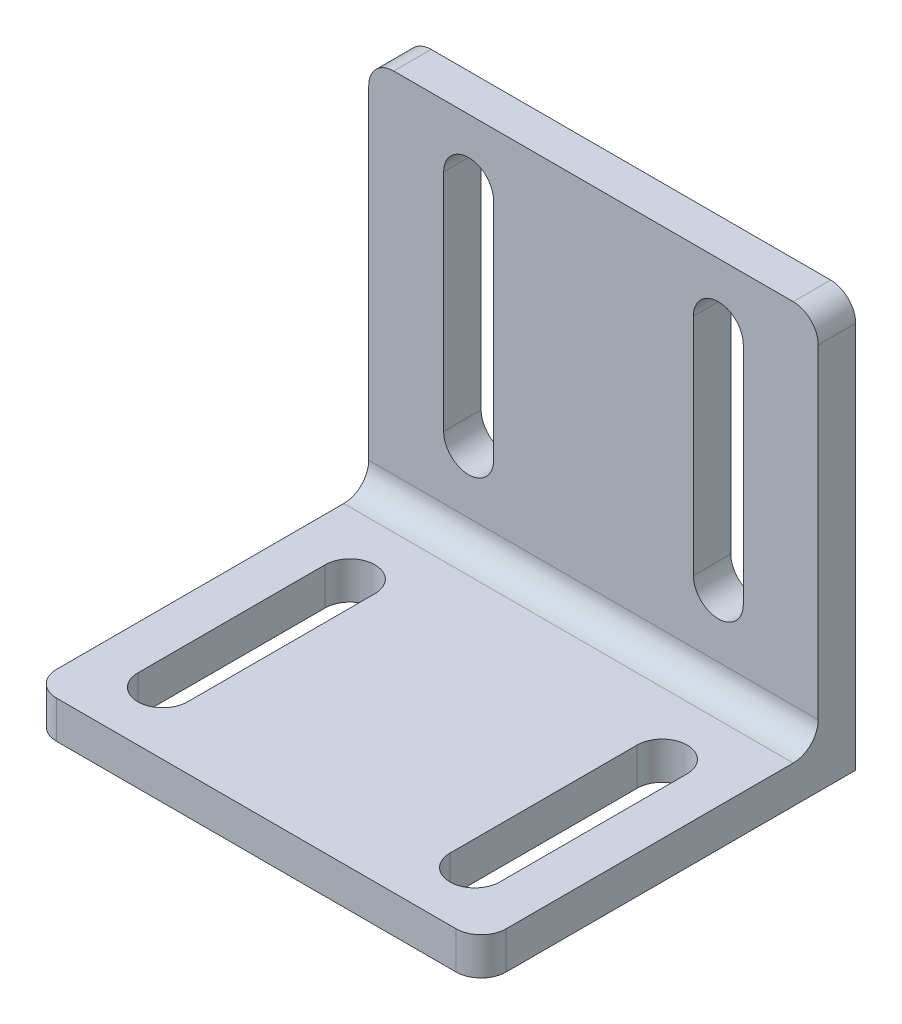
SolidWorks part; units mm, degrees
ref_plane "前视基准面" through (0, 0, 0) normal (0, 0, 1) x (1, 0, 0)
ref_plane "上视基准面" through (0, 0, 0) normal (0, 1, 0) x (1, 0, 0)
ref_plane "右视基准面" through (0, 0, 0) normal (1, 0, 0) x (0, 0, -1)
other "Configuration Table"
sketch "草图1" plane through (0, 0, 0) normal (0, 1, 0) x (1, 0, 0)
  line L0 (0, 14.1848) -> (0, -15.0978) construction
  line L1 (0, 9.4891) -> (-18, 9.4891)
  line L2 (-18, 9.4891) -> (-18, -20.5109)
  line L3 (-18, -20.5109) -> (0, -20.5109)
  line L4 (0, 9.4891) -> (18, 9.4891)
  line L5 (18, 9.4891) -> (18, -20.5109)
  line L6 (18, -20.5109) -> (0, -20.5109)
  line L7 (-12.5, -0.5109) -> (-12.5, -15.5109) construction
  line L8 (-10.5, -0.5109) -> (-10.5, -15.5109)
  line L9 (-14.5, -0.5109) -> (-14.5, -15.5109)
  line L10 (12.5, -0.5109) -> (12.5, -15.5109) construction
  line L11 (14.5, -0.5109) -> (14.5, -15.5109)
  line L12 (10.5, -0.5109) -> (10.5, -15.5109)
  arc A0 (-10.5, -0.5109) -> (-14.5, -0.5109) centre (-12.5, -0.5109) ccw
  arc A1 (-14.5, -15.5109) -> (-10.5, -15.5109) centre (-12.5, -15.5109) ccw
  arc A2 (14.5, -0.5109) -> (10.5, -0.5109) centre (12.5, -0.5109) ccw
  arc A3 (10.5, -15.5109) -> (14.5, -15.5109) centre (12.5, -15.5109) ccw
  point P11 (-12.5, -8.0109)
  point P16 (12.5, -8.0109)
  dimension "D6" = 2
  dimension "D7" = 2
  dimension "D8" = 5
  dimension "D9" = 5
  dimension "D1" = 18
  dimension "D2" = 30
  dimension "D3" = 18
  dimension "D4" = 25
  dimension "D5" = 12.5
  dimension "D10" = 15
  dimension "D11" = 15
extrude "凸台-拉伸1" add sketch "草图1" along normal blind 3
sketch "草图2" plane through (0, 3, 0) normal (0, 1, 0) x (1, 0, 0)
  line L0 (-18, 6.4891) -> (18, 6.4891)
  line L1 (-18, 9.4891) -> (-18, -20.5109) construction
  line L2 (18, -20.5109) -> (18, 9.4891) construction
  line L3 (18, 6.4891) -> (18, 9.4891)
  line L4 (18, 9.4891) -> (-18, 9.4891)
  line L5 (-18, 9.4891) -> (-18, 6.4891)
  dimension "D1" = 3
extrude "凸台-拉伸2" add sketch "草图2" along normal blind 30
sketch "草图3" plane through (0, 0, -6.4891) normal (0, 0, 1) x (1, 0, 0)
  line L0 (0, 38.4533) -> (0, -7.1758) construction
  line L1 (-10, 28) -> (-10, 10) construction
  line L2 (-8, 28) -> (-8, 10)
  line L3 (-12, 28) -> (-12, 10)
  line L6 (-18, 33) -> (18, 33) construction
  line L7 (10, 28) -> (10, 10) construction
  line L8 (8, 28) -> (8, 10)
  line L9 (12, 28) -> (12, 10)
  arc A0 (-8, 28) -> (-12, 28) centre (-10, 28) ccw
  arc A1 (-12, 10) -> (-8, 10) centre (-10, 10) ccw
  arc A2 (8, 28) -> (12, 28) centre (10, 28) cw
  arc A3 (12, 10) -> (8, 10) centre (10, 10) cw
  point P5 (-10, 19)
  point P12 (-11.1002, 33)
  point P13 (-11.9032, 33)
  point P16 (10, 19)
  dimension "D2" = 2
  dimension "D4" = 5
  dimension "D1" = 18
  dimension "D3" = 10
extrude "切除-拉伸1" cut sketch "草图3" against normal through all both
fillet "圆角1" radius 2 4 edges at (-18, 33, -7.9891) (18, 33, -7.9891) (18, 1.5, 20.5109) (-18, 1.5, 20.5109)
fillet "圆角2" radius 2 1 edges at (0, 3, -6.4891)
